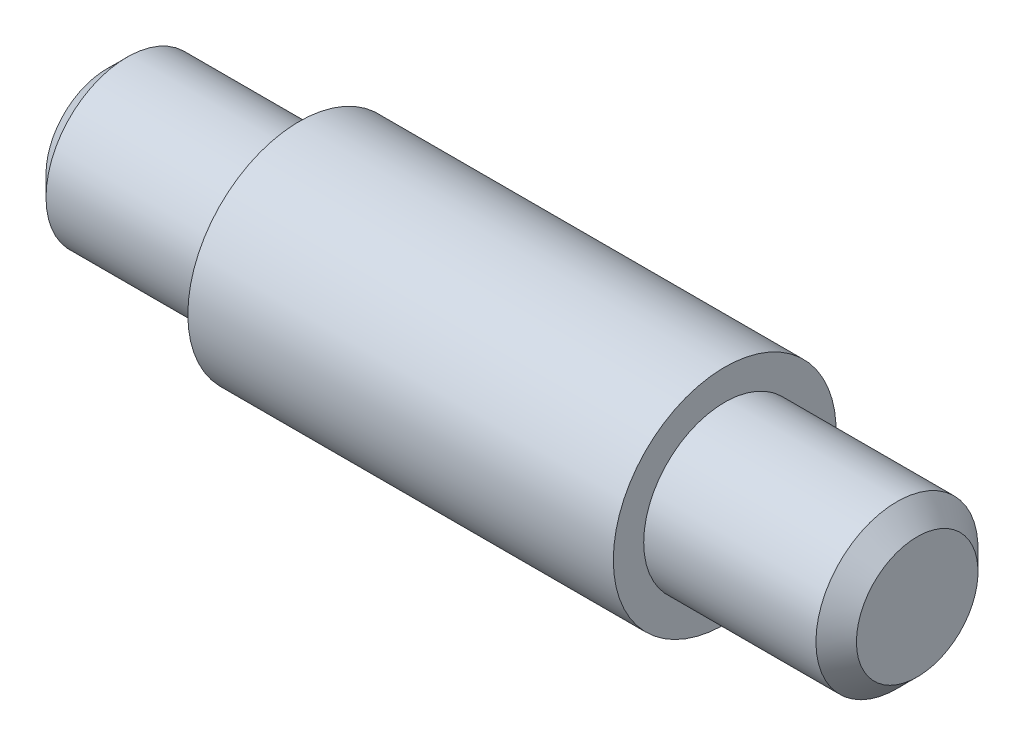
SolidWorks part; units mm, degrees
ref_plane "前基準面" through (0, 0, 0) normal (0, 0, 1) x (1, 0, 0)
ref_plane "上基準面" through (0, 0, 0) normal (0, 1, 0) x (1, 0, 0)
ref_plane "右基準面" through (0, 0, 0) normal (1, 0, 0) x (0, 0, -1)
sketch "草圖1" plane through (0, 0, 0) normal (0, 0, 1) x (1, 0, 0)
  line L0 (0, 0) -> (100.0148, 0) construction
  line L1 (0, 0) -> (0, 11)
  line L2 (0, 11) -> (21, 11)
  line L3 (21, 11) -> (21, 8)
  line L4 (21, 8) -> (40, 8)
  line L5 (40, 8) -> (40, 0)
  line L6 (40, 0) -> (0, 0)
  dimension "D1" = 16
  dimension "D2" = 22
  dimension "D3" = 40
  dimension "D4" = 21
revolve "旋轉1" add sketch "草圖1" angle 360 about L0
chamfer "導角1" distance 2 angle 45 1 edges at (40, 0, 8)
mirror "鏡射1" about plane through (0, 0, 0) normal (1, 0, 0) of bodies 101
